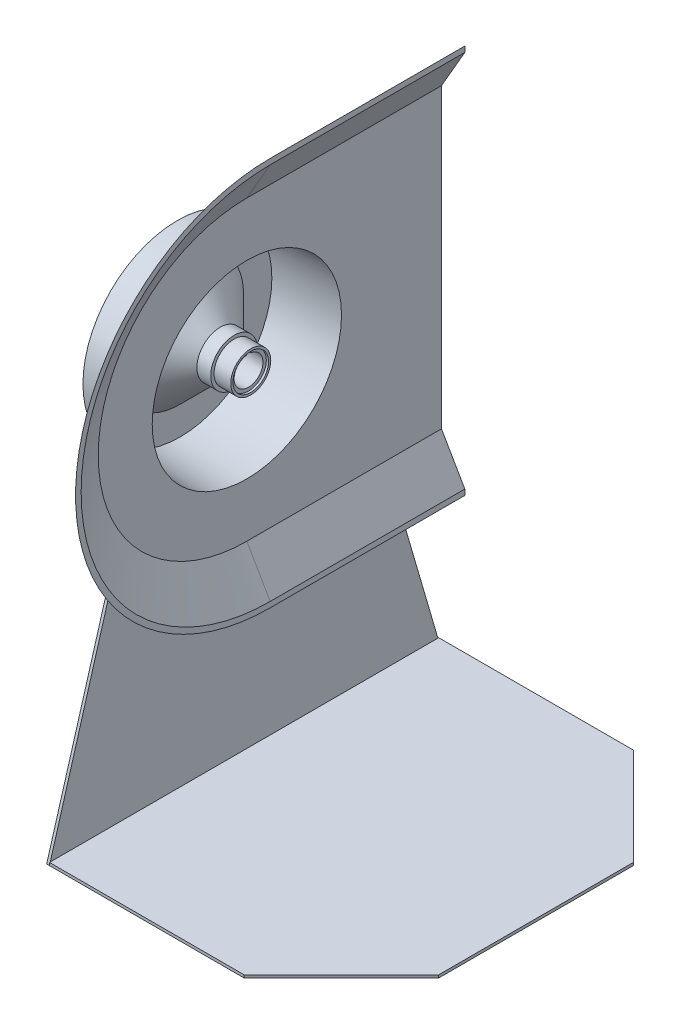
SolidWorks part; units mm, degrees
ref_plane "Plan de face" through (0, 0, 0) normal (0, 0, 1) x (1, 0, 0)
ref_plane "Plan de dessus" through (0, 0, 0) normal (0, 1, 0) x (1, 0, 0)
ref_plane "Plan de droite" through (0, 0, 0) normal (1, 0, 0) x (0, 0, -1)
sketch "Esquisse2" plane through (0, 0, 0) normal (0, 0, 1) x (1, 0, 0)
  line L0 (0, 350) -> (0, 0)
  line L5 (-47, 268.5936) -> (0, 350)
  line L6 (-47, 268.5936) -> (-47, 0)
  line L7 (-47, 0) -> (0, 0)
  dimension "D1" = 150
  dimension "D2" = 350
  dimension "D3" = 47
revolve "Revolve1" add sketch "Esquisse2" angle 180 about L7
sketch "Sketch12" plane through (-47, 0, 0) normal (-1, 0, 0) x (0, 0, 1)
  circle A0 centre (0, 0) radius 175
extrude "Boss-Extrude2" add sketch "Sketch12" along normal blind 120 draft 2.5
sketch "Sketch13" plane through (0, 0, 0) normal (0, 0, -1) x (-1, 0, 0)
  line L0 (0, 350) -> (47, 268.5936)
  line L1 (47, 268.5936) -> (47, -268.5936)
  line L2 (47, -268.5936) -> (0, -350)
  line L3 (0, -350) -> (0, 350)
extrude "Boss-Extrude3" add sketch "Sketch13" along normal blind 350
sketch "Sketch14" plane through (-167, 0, 0) normal (-1, 0, 0) x (0, 0, 1)
  circle A0 centre (0, 0) radius 112
extrude "Cut-Extrude1" cut sketch "Sketch14" against normal blind 32 draft 45 contours A0
sketch "Sketch17" plane through (-135, 0, 0) normal (-1, 0, 0) x (0, 0, 1)
  circle A0 centre (0, 0) radius 31
extrude "Cut-Extrude3" cut sketch "Sketch17" against normal blind 8
shell "Shell1" thickness 5
sketch "Sketch18" plane through (0, 0, 0) normal (0, 0, 1) x (1, 0, 0)
  line L0 (-130, 82.0711) -> (-89.9289, 42)
  line L1 (-89.9289, 42) -> (-65, 42)
  line L2 (-65, 42) -> (-65, 36)
  line L3 (-65, 36) -> (-35, 36)
  line L4 (-35, 36) -> (-35, 32)
  line L5 (-35, 32) -> (-39, 32)
  line L6 (-39, 32) -> (-39, 26)
  line L7 (-39, 26) -> (-122, 26)
  line L8 (-122, -36) -> (-122, 36) construction
  line L9 (-122, 26) -> (-122, 36)
  line L10 (-122, 36) -> (-130, 36)
  line L11 (-130, 36) -> (-130, 82.0711)
  line L13 (0, 0) -> (-213.9916, 0) construction
  line L14 (-130, 82.0711) -> (-162, 114.0711) construction
  point P21 (-39, 29)
  dimension "D1" = 26
  dimension "D2" = 26
  dimension "D3" = 91
  dimension "D4" = 4
  dimension "D5" = 42
  dimension "D6" = 32
  dimension "D7" = 36
sketch "Sketch15" plane through (-135, 0, 0) normal (-1, 0, 0) x (0, 0, 1)
  circle A0 centre (0, 0) radius 26
extrude "Cut-Extrude2" cut sketch "Sketch15" against normal through all
revolve "Revolve2" add sketch "Sketch18" angle 360 about L13
sketch "Sketch19" plane through (0, 0, 0) normal (0, 0, 1) x (1, 0, 0)
  line L0 (0, 0) -> (-197.0961, 0) construction
  line L1 (0, -350) -> (0, 350) construction
sketch "Sketch20" plane through (-47, 0, 0) normal (-1, 0, 0) x (0, 0, 1)
  line L1 (-350, -600) -> (350, -600)
  line L3 (175, 0) -> (350, -600)
  line L4 (-175, 0) -> (-350, -600)
  arc A0 (-175, 0) -> (175, 0) centre (0, 0) ccw
  circle A1 centre (0, 0) radius 175 construction
  point P6 (0, -600)
  dimension "D1" = 600
  dimension "D2" = 700
  dimension "D3" = 0
  dimension "D4" = 0
  dimension "D5" = 350
extrude "Boss-Extrude4" add sketch "Sketch20" along normal blind 5 contours L3 L1 L4 A0
sketch "Sketch21" plane through (0, -600, 0) normal (0, -1, 0) x (1, 0, 0)
  line L2 (-47, 350) -> (-47, -350)
  line L5 (-47, 350) -> (303, 350)
  line L6 (303, 350) -> (478, 175)
  line L7 (478, 175) -> (478, -175)
  line L8 (478, -175) -> (303, -350)
  line L9 (303, -350) -> (-47, -350)
  line L10 (478, 0) -> (0, 0) construction
  dimension "D1" = 700
  dimension "D2" = 135
  dimension "D3" = 135
  dimension "D4" = 350
  dimension "D5" = 350
  dimension "D6" = 350
  dimension "D7" = 90
extrude "Boss-Extrude5" add sketch "Sketch21" against normal blind 5 contours L5 L6 L7 L8 L9 L2
sketch "Esquisse3" plane through (-127, 0, 0) normal (-1, 0, 0) x (0, 0, 1)
  line L1 (-4, 30) -> (4, 30)
  line L2 (-4, 30) -> (-4, 26)
  line L4 (4, 30) -> (4, 26)
  line L6 (4, 26) -> (4, 25)
  line L7 (4, 25) -> (-4, 25)
  line L8 (-4, 26) -> (-4, 25)
  point P4 (0, 30)
  dimension "D2" = 4
  dimension "D3" = 8
  dimension "D4" = 0
  dimension "D1" = 26
  dimension "D5" = 1
  dimension "D6" = 1
extrude "Enlèv. mat.-Extru.2" cut sketch "Esquisse3" against normal up to next contours L2 L8 L7 L6 L4 L1
equation "\"D4@Esquisse3\"=0"
